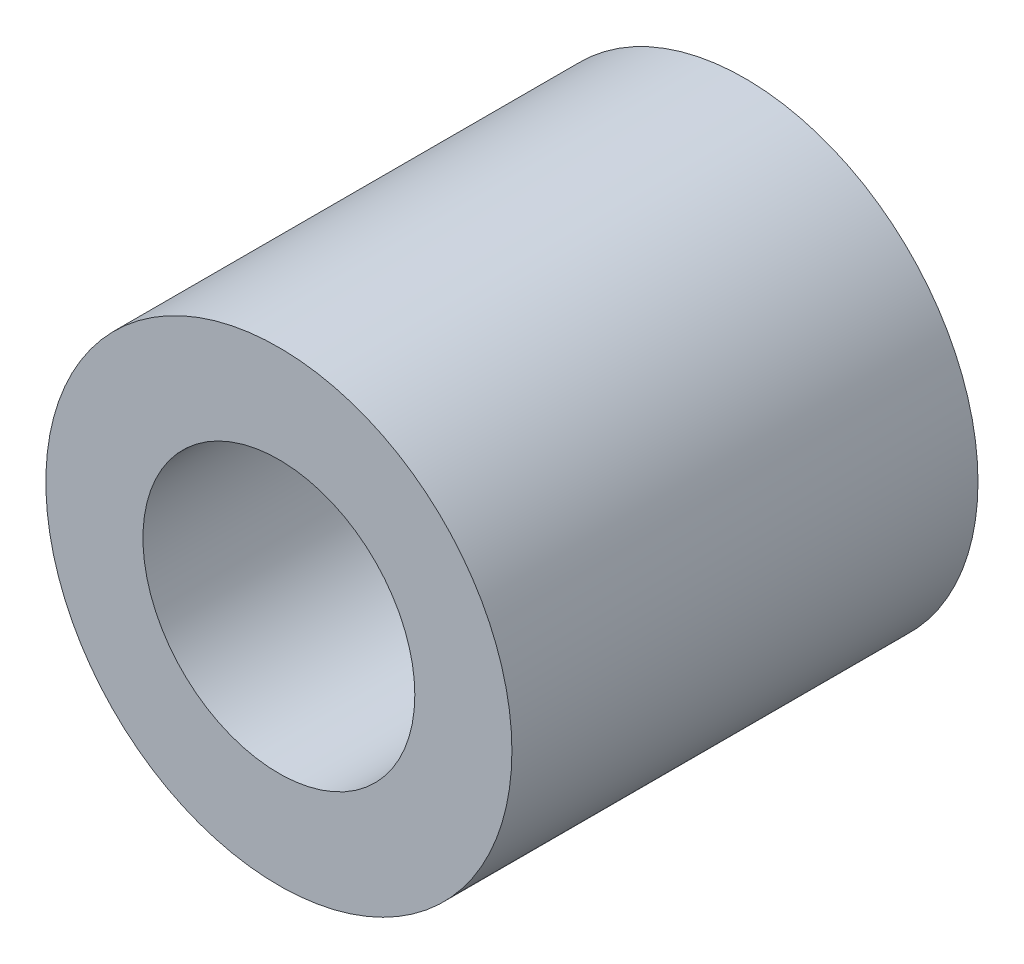
SolidWorks part; units mm, degrees
ref_plane "前视基准面" through (0, 0, 0) normal (0, 0, 1) x (1, 0, 0)
ref_plane "上视基准面" through (0, 0, 0) normal (0, 1, 0) x (1, 0, 0)
ref_plane "右视基准面" through (0, 0, 0) normal (1, 0, 0) x (0, 0, -1)
sketch "草图1" plane through (0, 0, 0) normal (0, 0, 1) x (1, 0, 0)
  circle A0 centre (0, 0) radius 3.5
  circle A1 centre (0, 0) radius 6
extrude "凸台-拉伸1" add sketch "草图1" along normal blind 12
